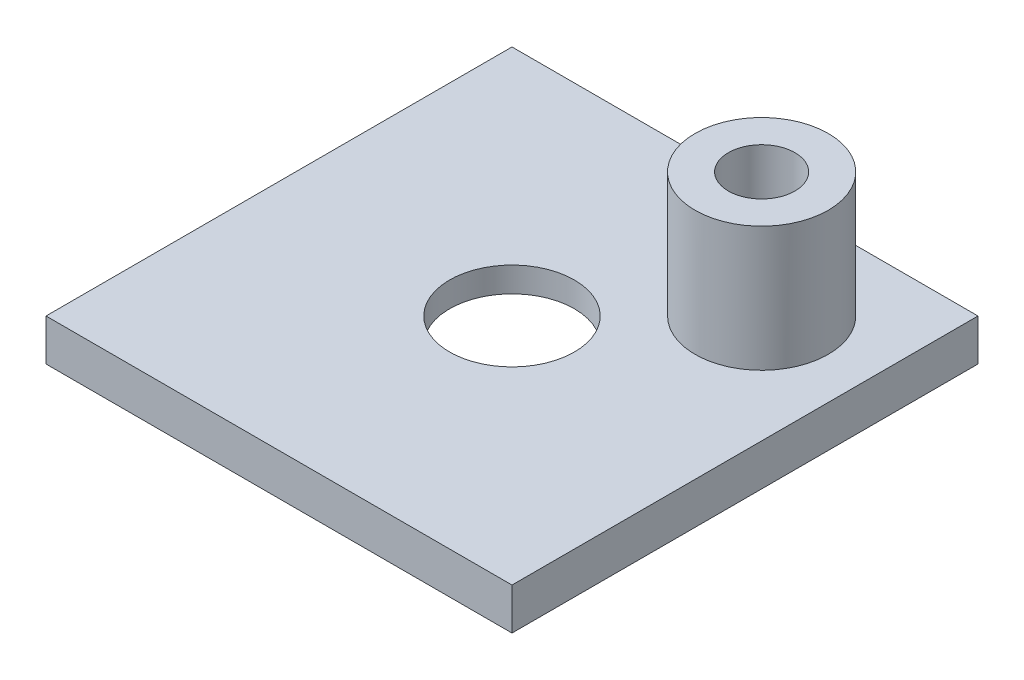
SolidWorks part; units mm, degrees
ref_plane "Front Plane" through (0, 0, 0) normal (0, 0, 1) x (1, 0, 0)
ref_plane "Top Plane" through (0, 0, 0) normal (0, 1, 0) x (1, 0, 0)
ref_plane "Right Plane" through (0, 0, 0) normal (1, 0, 0) x (0, 0, -1)
sketch "Sketch1" plane through (0, 0, 0) normal (0, 1, 0) x (1, 0, 0)
  line L1 (-28, -28) -> (28, -28)
  line L2 (-28, -28) -> (-28, 28)
  line L3 (-28, 28) -> (28, 28)
  line L4 (28, -28) -> (28, 28)
  line L5 (-28, -28) -> (28, 28) construction
  line L6 (-28, 28) -> (28, -28) construction
  point P0 (0, 0)
  dimension "D1" = 56
  dimension "D2" = 56
extrude "Boss-Extrude1" add sketch "Sketch1" along normal blind 5
sketch "Sketch2" plane through (0, 5, 0) normal (0, 1, 0) x (1, 0, 0)
  circle A0 centre (15, 15) radius 8
  point P2 (0, 0)
  dimension "D1" = 16
  dimension "D2" = 15
  dimension "D3" = 15
extrude "Boss-Extrude2" add sketch "Sketch2" along normal blind 15
sketch "Sketch4" plane through (0, 0, 0) normal (0, -1, 0) x (1, 0, 0)
  circle A0 centre (0, 0) radius 19
  dimension "D1" = 38
extrude "Cut-Extrude2" cut sketch "Sketch4" against normal blind 2
sketch "Sketch5" plane through (0, 2, 0) normal (0, -1, 0) x (1, 0, 0)
  circle A0 centre (0, 0) radius 7.5
  dimension "D1" = 15
extrude "Cut-Extrude3" cut sketch "Sketch5" against normal through all and the other way through all
sketch "Sketch6" plane through (0, 20, 0) normal (0, 1, 0) x (1, 0, 0)
  circle A0 centre (15, 15) radius 4
  dimension "D1" = 8
extrude "Cut-Extrude4" cut sketch "Sketch6" along direction (0, -1, 0) on the side against the normal up to surface (15 mm away)
